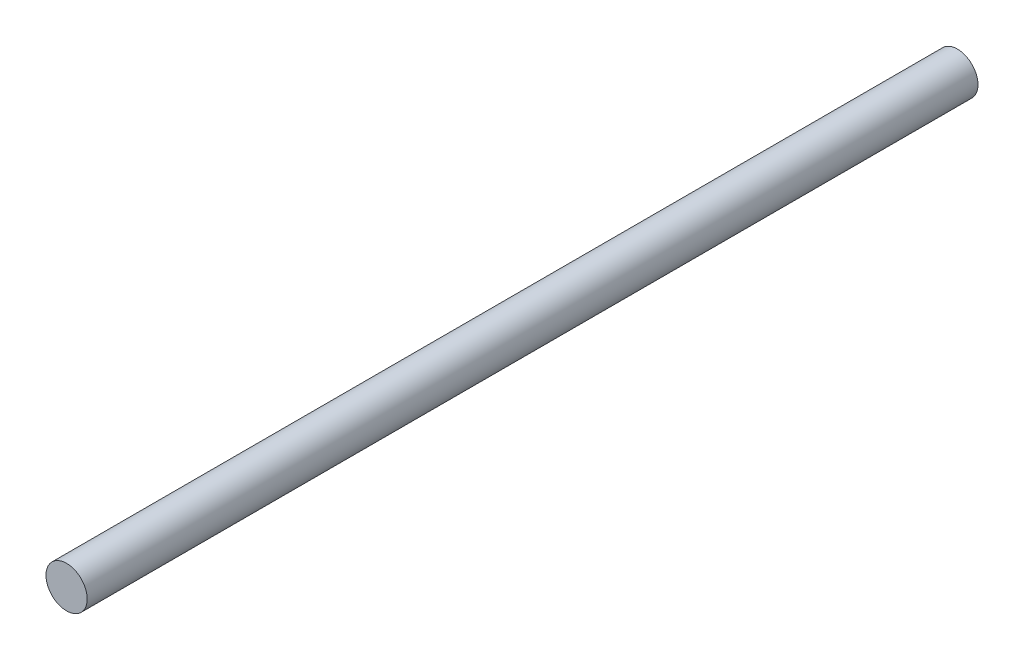
SolidWorks part; units mm, degrees
ref_plane "Plano frontal" through (0, 0, 0) normal (0, 0, 1) x (1, 0, 0)
ref_plane "Plano superior" through (0, 0, 0) normal (0, 1, 0) x (1, 0, 0)
ref_plane "Plano direito" through (0, 0, 0) normal (1, 0, 0) x (0, 0, -1)
sketch "Esboço1" plane through (0, 0, 0) normal (0, 0, 1) x (1, 0, 0)
  circle A0 centre (-1.4221, 0.6518) radius 1.25
  dimension "D1" = 2.5
extrude "Ressalto-extrusão1" add sketch "Esboço1" along normal blind 54
